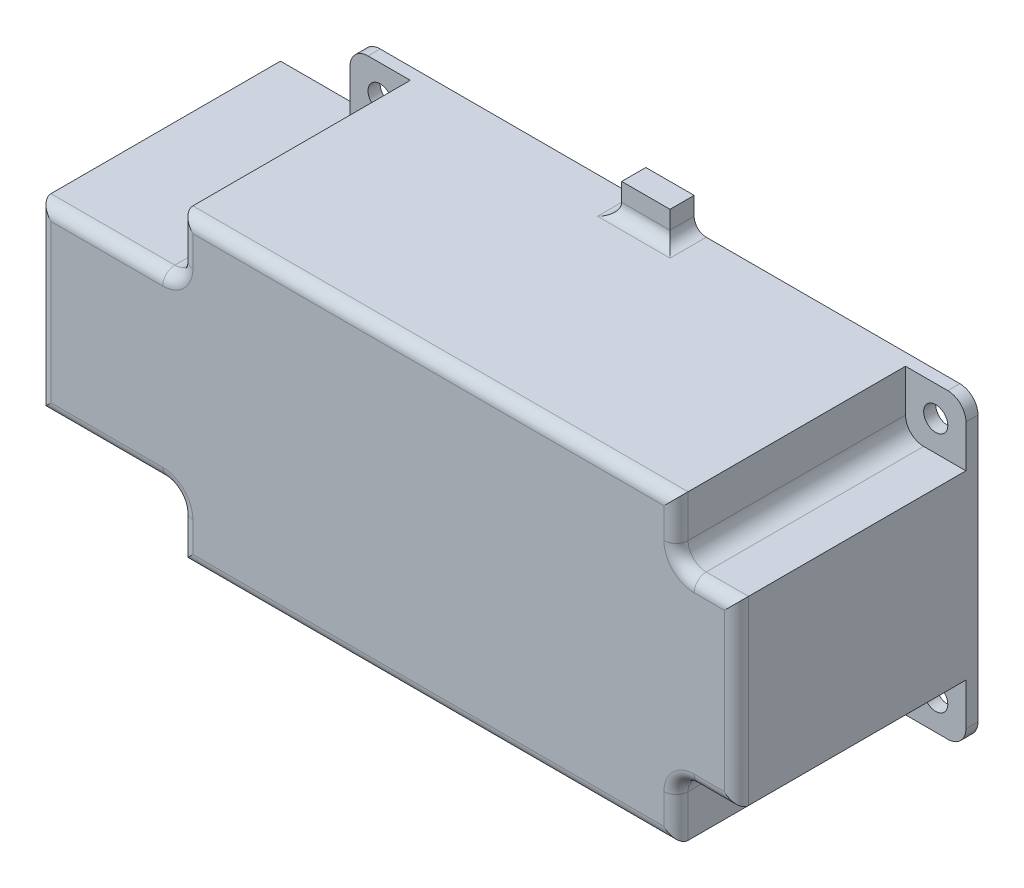
SolidWorks part; units mm, degrees
ref_plane "Alzado" through (0, 0, 0) normal (0, 0, 1) x (1, 0, 0)
ref_plane "Planta" through (0, 0, 0) normal (0, 1, 0) x (1, 0, 0)
ref_plane "Vista lateral" through (0, 0, 0) normal (1, 0, 0) x (0, 0, -1)
sketch "Croquis1" plane through (0, 0, 0) normal (0, 0, 1) x (1, 0, 0)
  line L1 (-51, 25) -> (51, 25)
  line L2 (-51, 25) -> (-51, -25)
  line L3 (-51, -25) -> (51, -25)
  line L4 (51, 25) -> (51, -25)
  line L5 (-51, 25) -> (51, -25) construction
  line L6 (-51, -25) -> (51, 25) construction
  point P0 (0, 0)
extrude "Saliente-Extruir1" add sketch "Croquis1" along normal blind 40
sketch "Croquis3" plane through (0, 0, 40) normal (0, 0, 1) x (1, 0, 0)
  line L0 (-51, -25) -> (-51, -15) construction
  line L1 (-51, 25) -> (-51, -25) construction
  line L2 (-51, -15) -> (-44, -15)
  line L3 (-41, -18) -> (-41, -25)
  line L4 (-51, -25) -> (51, -25) construction
  line L5 (-41, 25) -> (-41, 18)
  line L6 (51, 25) -> (-51, 25) construction
  line L7 (-51, 15) -> (-44, 15)
  line L8 (51, 15) -> (44, 15)
  line L9 (51, -25) -> (51, 25) construction
  line L10 (41, 25) -> (41, 18)
  line L11 (41, -25) -> (41, -18)
  line L12 (44, -15) -> (51, -15)
  line L14 (51, -25) -> (-51, -25)
  line L15 (51, -25) -> (51, 25)
  line L16 (51, 25) -> (-51, 25)
  line L17 (-51, -25) -> (-51, 25)
  line L18 (51, -25) -> (-51, 25) construction
  line L19 (51, 25) -> (-51, -25) construction
  arc A0 (44, 15) -> (41, 18) centre (44, 18) cw
  arc A1 (41, -18) -> (44, -15) centre (44, -18) cw
  arc A2 (-44, -15) -> (-41, -18) centre (-44, -18) cw
  arc A3 (-41, 18) -> (-44, 15) centre (-44, 18) cw
  point P21 (0, 0)
  point P30 (41, 15)
  point P35 (-41, -15)
  point P38 (-41, 15)
  line M14 (51, -25) -> (51, 25)
  line M15 (51, 25) -> (-51, 25)
  line M16 (-51, 25) -> (-51, -25)
  line M17 (-51, -25) -> (51, -25)
  dimension "D1" = 3
extrude "Cortar-Extruir1" cut sketch "Croquis3" against normal blind 38 contours A0 L8 L10 M14 M15 | A1 L11 L12 M17 M14 | A2 L2 L3 M16 M17 | A3 L5 L7 M15 M16
sketch "Croquis4" plane through (0, 0, 2) normal (0, 0, 1) x (1, 0, 0)
  line L0 (-46, -20) -> (-51, -20) construction
  line L1 (-48, -25) -> (48, -25)
  line L2 (-51, -22) -> (-51, 22)
  line L3 (-48, 25) -> (48, 25)
  line L4 (51, -22) -> (51, 22)
  line L5 (-46, -25) -> (-46, -20) construction
  line L6 (51, -20) -> (46, -20) construction
  line L7 (46, 25) -> (46, 20) construction
  line L8 (-51, 20) -> (-46, 20) construction
  line L10 (-51, -25) -> (51, -25)
  line L11 (-51, -25) -> (-51, 25)
  line L12 (-51, 25) -> (51, 25)
  line L13 (51, -25) -> (51, 25)
  arc A0 (48, -25) -> (51, -22) centre (48, -22) ccw
  arc A1 (48, 25) -> (51, 22) centre (48, 22) cw
  arc A2 (-51, 22) -> (-48, 25) centre (-48, 22) cw
  arc A3 (-48, -25) -> (-51, -22) centre (-48, -22) cw
  circle A4 centre (-46, 20) radius 2
  circle A5 centre (-46, -20) radius 2
  circle A6 centre (46, -20) radius 2
  circle A7 centre (46, 20) radius 2
  point P10 (51, 25)
  point P15 (-51, -25)
  line M15 (-51, -15) -> (-51, -25)
  line M16 (-51, -25) -> (-41, -25)
  dimension "D1" = 3
extrude "Cortar-Extruir2" cut sketch "Croquis4" against normal blind 18 contours A3 M16 M15 | A5 | L11 A2 L12 | A4 | A7 | L12 A1 L13 | A6 | A0 L10 L13
sketch "Croquis5" plane through (0, 0, 0) normal (0, 0, -1) x (-1, 0, 0)
  line L0 (39.5, -15.4722) -> (39.5, -25) construction
  line L1 (51, -13.4722) -> (41.5, -13.4722) construction
  line L2 (51, 22) -> (51, -22) construction
  line L3 (48, -25) -> (-48, -25) construction
  line L4 (39.5, 25) -> (39.5, 15.5) construction
  line L5 (-48, 25) -> (48, 25) construction
  line L6 (51, 13.5) -> (41.5, 13.5) construction
  line L7 (-51, -13.4722) -> (-41.4905, -13.4722) construction
  line L8 (-51, -22) -> (-51, 22) construction
  line L9 (-39.4905, -25) -> (-39.4905, -15.4722) construction
  line L10 (-39.4905, 15.5) -> (-39.4905, 25) construction
  line L11 (-41.4905, 13.5) -> (-51, 13.5) construction
  line L12 (51, 0) -> (49.4746, 0) construction
  line L13 (0, -25) -> (0, -23.5) construction
  line L14 (-51, 0) -> (-49.5254, 0) construction
  line L15 (0, 25) -> (0, 23.5) construction
  line L16 (0, 23.5) -> (-39.4905, 23.5)
  line L17 (49.4746, 13.5) -> (49.4746, -13.4722)
  line L18 (49.4746, -13.4722) -> (41.5, -13.4722)
  line L19 (39.5, -15.4722) -> (39.5, -23.5)
  line L20 (39.5, -23.5) -> (-39.4905, -23.5)
  line L21 (-39.4905, -23.5) -> (-39.4905, -15.4722)
  line L22 (-41.4905, -13.4722) -> (-49.5254, -13.4722)
  line L23 (-49.5254, -13.4722) -> (-49.5254, 13.5)
  line L24 (-49.5254, 13.5) -> (-41.4905, 13.5)
  line L25 (-39.4905, 15.5) -> (-39.4905, 23.5)
  line L26 (49.4746, 13.5) -> (41.5, 13.5)
  line L27 (39.5, 15.5) -> (39.5, 23.5)
  line L28 (39.5, 23.5) -> (0, 23.5)
  line L29 (-51, -15.4722) -> (-39.4905, -15.4722) construction
  line L30 (-51, 15.5) -> (-39.4905, 15.5) construction
  line L31 (-41.4905, 25) -> (-41.4905, 13.5) construction
  line L32 (41.5, 25) -> (41.5, 13.5) construction
  line L33 (51, 15.5) -> (39.5, 15.5) construction
  line L34 (51, -15.4722) -> (39.5, -15.4722) construction
  line L35 (41.5, -25) -> (41.5, -13.5) construction
  line L36 (-41.4905, -25) -> (-41.4905, -13.4722) construction
  arc A0 (39.5, 15.5) -> (41.5, 13.5) centre (41.5, 15.5) ccw
  arc A1 (41.5, -13.4722) -> (39.5, -15.4722) centre (41.5, -15.4722) ccw
  arc A2 (-41.4905, -13.4722) -> (-39.4905, -15.4722) centre (-41.4905, -15.4722) cw
  arc A3 (-39.4905, 15.5) -> (-41.4905, 13.5) centre (-41.4905, 15.5) cw
  point P34 (39.5, -13.4722)
  point P37 (-39.4905, -13.4722)
  dimension "D1" = 2
extrude "Cortar-Extruir3" cut sketch "Croquis5" against normal blind 38
sketch "Croquis7" plane through (0, 25, 0) normal (0, 1, 0) x (1, 0, 0)
  line L0 (0, -3) -> (3, -3) construction
  line L1 (0, -3) -> (0, 0) construction
  line L2 (48, 0) -> (-48, 0) construction
  line L3 (0, -3) -> (-3, -3) construction
  line L4 (3, 0) -> (3, -3)
  line L5 (3, -3) -> (-3, -3)
  line L6 (-3, -3) -> (-3, 0)
  line L7 (3, 0) -> (-3, 0)
extrude "Cortar-Extruir5" cut sketch "Croquis7" against normal blind 10
sketch "Croquis8" plane through (0, 25, 0) normal (0, 1, 0) x (1, 0, 0)
  line L0 (3, 0) -> (4, 0)
  line L1 (48, 0) -> (3, 0) construction
  line L2 (4, 0) -> (4, -4)
  line L3 (4, -4) -> (-4, -4)
  line L4 (-4, -4) -> (-4, 0)
  line L5 (-3, 0) -> (-48, 0) construction
  line L6 (-4, 0) -> (-3, 0)
  line L7 (-3, 0) -> (-3, -3)
  line L8 (-3, -3) -> (3, -3)
  line L9 (3, -3) -> (3, 0)
extrude "Saliente-Extruir2" add sketch "Croquis8" along normal blind 5
sketch "Croquis9" plane through (0, 0, 3) normal (0, 0, -1) x (-1, 0, 0)
  line L0 (3, 23.5) -> (3, 30) construction
  line L1 (-3, 30) -> (3, 30)
  line L2 (-3, 30) -> (-3, 29)
  line L3 (-3, 29) -> (3, 29)
  line L4 (3, 30) -> (3, 29)
extrude "Saliente-Extruir3" add sketch "Croquis9" along normal blind 3
fillet "Redondeo2" radius 2 1 edges at (0, 23.5, 3)
fillet "Redondeo4" radius 2 3 edges at (-4, 25, 2) (0, 25, 4) (4, 25, 2)
sketch "Croquis16" plane through (-49.4746, 0, 0) normal (1, 0, 0) x (0, 0, -1)
  line L0 (0, 0.0139) -> (-1.5, 0.0139) construction
  line L1 (0, -13.4722) -> (0, 13.5) construction
  line L2 (-38, 13.5) -> (0, 13.5) construction
  line L3 (-1.5, 13.5) -> (-38, 13.5)
  line L4 (-1.5, 13.5) -> (-1.5, -13.4722)
  line L5 (-1.5, -13.4722) -> (-38, -13.4722)
  line L6 (-38, 13.5) -> (-38, -13.4722)
extrude "Cortar-Extruir13" cut sketch "Croquis16" against normal blind 5.5
sketch "Croquis17" plane through (-51, 0, 0) normal (-1, 0, 0) x (0, 0, 1)
  line L0 (2, -15) -> (0, -15) construction
  line L1 (0, 22) -> (0, -22) construction
  line L3 (0, -15) -> (40, -15)
  line L4 (0, -15) -> (0, 15)
  line L5 (0, 15) -> (40, 15)
  line L6 (40, -15) -> (40, 15)
  line L7 (38, 13.5) -> (1.5, 13.5)
  line L8 (38, 13.5) -> (38, -13.4722)
  line L9 (38, -13.4722) -> (1.5, -13.4722)
  line L10 (1.5, 13.5) -> (1.5, -13.4722)
extrude "Saliente-Extruir7" add sketch "Croquis17" along normal blind 13.5
sketch "Croquis18" plane through (0, 13.5, 0) normal (0, -1, 0) x (1, 0, 0)
  line L0 (-64.5, 38) -> (-41.5, 38) construction
  line L1 (-64.5, 1.5) -> (-63, 1.5)
  line L2 (-64.5, 1.5) -> (-64.5, 38)
  line L3 (-64.5, 38) -> (-63, 38)
  line L4 (-63, 1.5) -> (-63, 38)
extrude "Saliente-Extruir8" add sketch "Croquis18" along normal blind 27.5
sketch "Croquis19" plane through (-64.5, 0, 0) normal (-1, 0, 0) x (0, 0, 1)
  line L0 (40, 0) -> (0, 0) construction
  line L1 (40, -15) -> (40, 15) construction
  line L2 (0, 15) -> (0, -15) construction
  circle A0 centre (20, 0) radius 11
extrude "Cortar-Extruir14" cut sketch "Croquis19" against normal blind 27.5
fillet "Redondeo5" radius 2 16 edges at (-41.8787, 15.8787, 40) (-41, 21.5, 40) (0, 25, 40) (41, 21.5, 40) (41.8787, 15.8787, 40) (47.5, 15, 40) (51, 0, 40) (47.5, -15, 40) (41.8787, -15.8787, 40) (41, -21.5, 40) (0, -25, 40) (-41, -21.5, 40) (-41.8787, -15.8787, 40) (-54.25, -15, 40) (-64.5, 0, 40) (-54.25, 15, 40)
